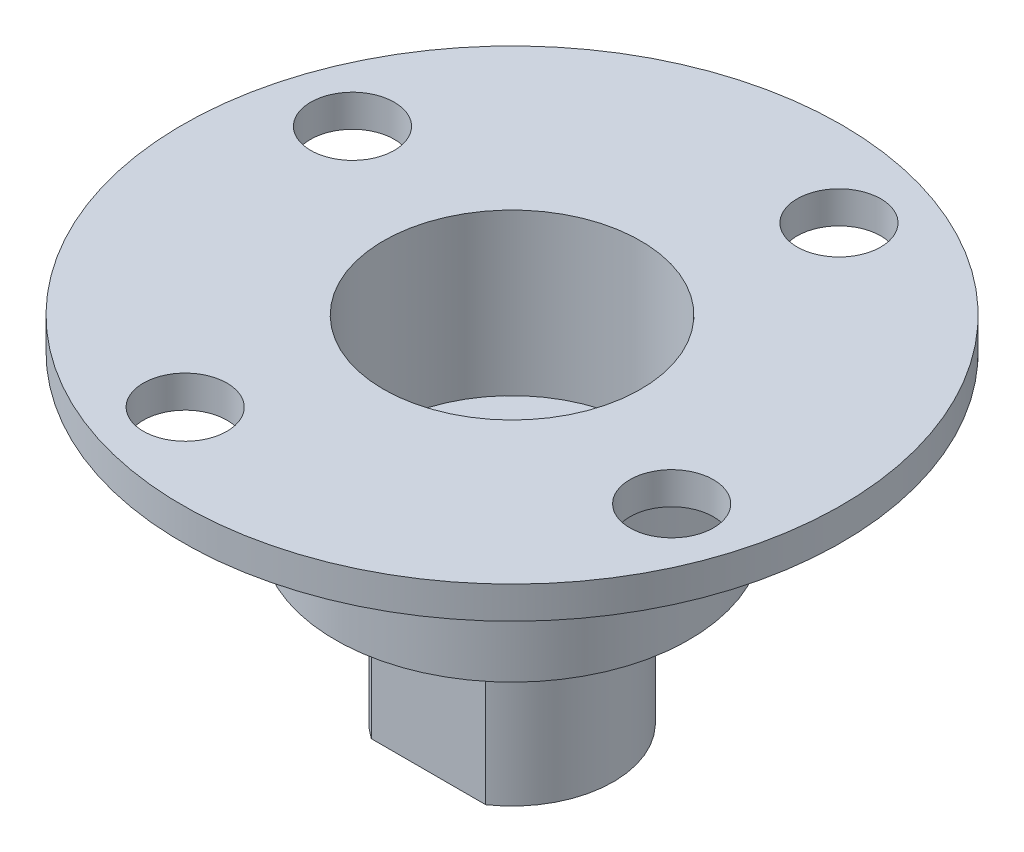
SolidWorks part; units mm, degrees
material "ABS"
ref_plane "Plan de face" through (0, 0, 0) normal (0, 0, 1) x (1, 0, 0)
ref_plane "Plan de dessus" through (0, 0, 0) normal (0, 1, 0) x (1, 0, 0)
ref_plane "Plan de droite" through (0, 0, 0) normal (1, 0, 0) x (0, 0, -1)
sketch "Esquisse1" plane through (0, -38.6013, 0) normal (0, -1, 0) x (1, 0, 0)
  circle A0 centre (14.0172, 17.25) radius 10.25
  arc A1 (9.5205, 8.039) -> (18.514, 26.461) centre (14.0172, 17.25) ccw construction
  dimension "D1" = 20.5
  dimension "D2" = 0
extrude "Boss.-Extru.1" add sketch "Esquisse1" along normal blind 1
hole_wizard "Dégagement M21" positions "Esquisse3" profile "Esquisse4" hole size "M2" standard "Ansi Metric" end condition up to next
sketch "Esquisse3" plane through (0, -39.6013, 0) normal (0, -1, 0) x (-1, 0, 0)
  circle A0 centre (-14.0172, -17.25) radius 8 construction
  point P0 (-11.4155, -24.8151)
  dimension "D1" = 16
sketch "Esquisse4" plane through (11.4155, -39.6013, 24.8151) normal (1, 0, 0) x (0, 0, -1)
  line L0 (0, 0) -> (0, 1.001)
  line L1 (0, 1.001) -> (1.3, 1.001)
  line L2 (1.3, 1.001) -> (1.3, 0)
  line L5 (1.3, 0) -> (0, 0)
  line L11 (0, -6.35) -> (0, 107.95) construction
  dimension "Diamètre du perçage jusqu'au prochain" = 2.6
  dimension "Profondeur du perçage jusqu'au prochain" = 1.001
pattern_circular "Répétition circulaire1" count 4 over 360 about axis through (14.0172, 0, 17.25) along (0, 1, 0) of "Dégagement M21"
sketch "Esquisse9" plane through (0, -39.6013, 0) normal (0, -1, 0) x (-1, 0, 0)
  circle A0 centre (-14.0172, -17.25) radius 5.5
  dimension "D1" = 11
extrude "Boss.-Extru.4" add sketch "Esquisse9" along normal blind 5
sketch "Esquisse10" plane through (0, -44.6013, 0) normal (0, -1, 0) x (1, 0, 0)
  line L0 (12.2389, 19.85) -> (15.7956, 19.85)
  arc A0 (12.2389, 19.85) -> (15.7956, 19.85) centre (14.0172, 17.25) ccw
  dimension "D1" = 6.3
  dimension "D2" = 2.6
fillet "Congé1" radius 0.5 1 edges at (14.0172, -39.6013, 11.75)
sketch "Esquisse11" plane through (0, -38.6013, 0) normal (0, 1, 0) x (1, 0, 0)
  circle A0 centre (14.0172, -17.25) radius 4
  circle A1 centre (14.0172, -17.25) radius 10.25 construction
  dimension "D1" = 8
extrude "Enlèv. mat.-Extru.2" cut sketch "Esquisse11" against normal blind 5
extrude "Boss.-Extru.5" add sketch "Esquisse10" along normal blind 5
